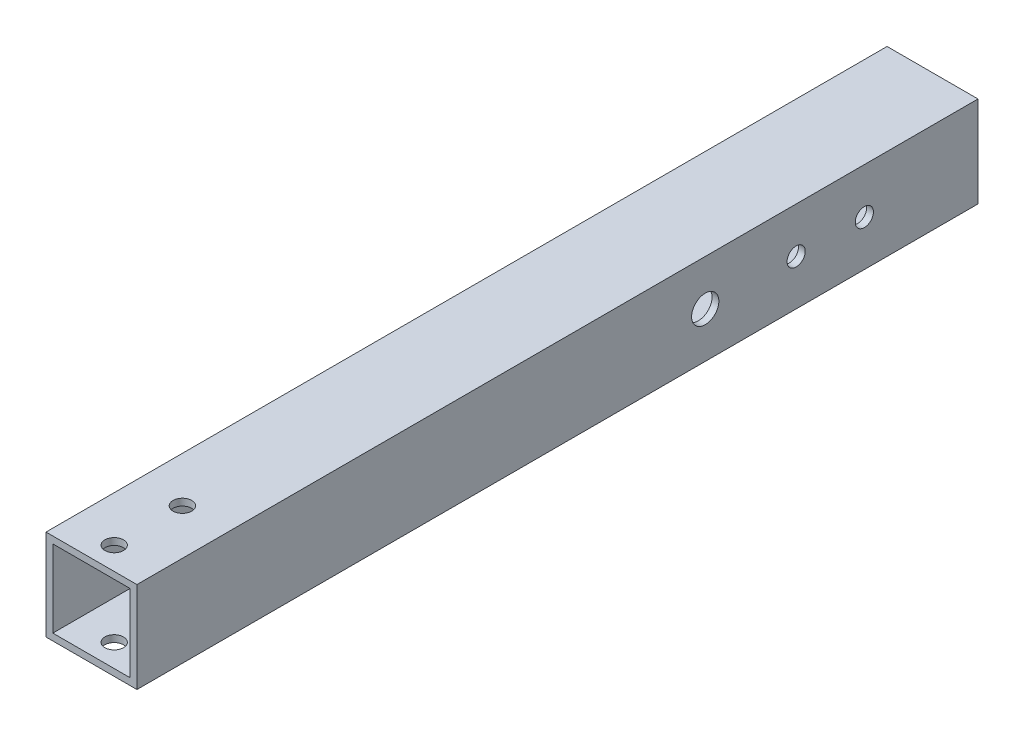
SolidWorks part; units mm, degrees
ref_plane "前视基准面" through (0, 0, 0) normal (0, 0, 1) x (1, 0, 0)
ref_plane "上视基准面" through (0, 0, 0) normal (0, 1, 0) x (1, 0, 0)
ref_plane "右视基准面" through (0, 0, 0) normal (1, 0, 0) x (0, 0, -1)
sketch "草图1" plane through (0, 0, 0) normal (0, 0, 1) x (1, 0, 0)
  line L1 (-10, 10) -> (10, 10)
  line L2 (-10, 10) -> (-10, -10)
  line L3 (-10, -10) -> (10, -10)
  line L4 (10, 10) -> (10, -10)
  line L5 (-10, 10) -> (10, -10) construction
  line L6 (-10, -10) -> (10, 10) construction
  line L7 (-8.5, 8.5) -> (8.5, 8.5)
  line L8 (-8.5, 8.5) -> (-8.5, -8.5)
  line L9 (-8.5, -8.5) -> (8.5, -8.5)
  line L10 (8.5, 8.5) -> (8.5, -8.5)
  line L11 (-8.5, 8.5) -> (8.5, -8.5) construction
  line L12 (-8.5, -8.5) -> (8.5, 8.5) construction
  point P0 (0, 0)
  point P5 (0, 0)
  point P11 (10, 0)
  dimension "D1" = 20
  dimension "D2" = 20
  dimension "D3" = 1.5
  dimension "D4" = 1.5
extrude "凸台-拉伸1" add sketch "草图1" along normal blind 185
sketch "草图2" plane through (0, 10, 0) normal (0, 1, 0) x (1, 0, 0)
  line L1 (10, -185) -> (-10, -185) construction
  circle A0 centre (0, -180) radius 2.05
  circle A1 centre (0, -165) radius 2.05
  dimension "D1" = 4.1
  dimension "D2" = 5
  dimension "D3" = 15
extrude "切除-拉伸1" cut sketch "草图2" against normal through all
sketch "草图3" plane through (10, 0, 0) normal (1, 0, 0) x (0, 0, -1)
  circle A0 centre (-25, 0) radius 2
  circle A1 centre (-40, 0) radius 2
  dimension "D1" = 4
  dimension "D2" = 25
  dimension "D3" = 15
extrude "切除-拉伸2" cut sketch "草图3" against normal through all
sketch "草图4" plane through (-10, 0, 0) normal (-1, 0, 0) x (0, 0, 1)
  line L0 (185, 10) -> (0, 10) construction
  line L1 (0, 10) -> (0, -10) construction
  circle A0 centre (60, 0) radius 3
  dimension "D1" = 6
  dimension "D2" = 10
  dimension "D3" = 60
extrude "切除-拉伸3" cut sketch "草图4" against normal through all
